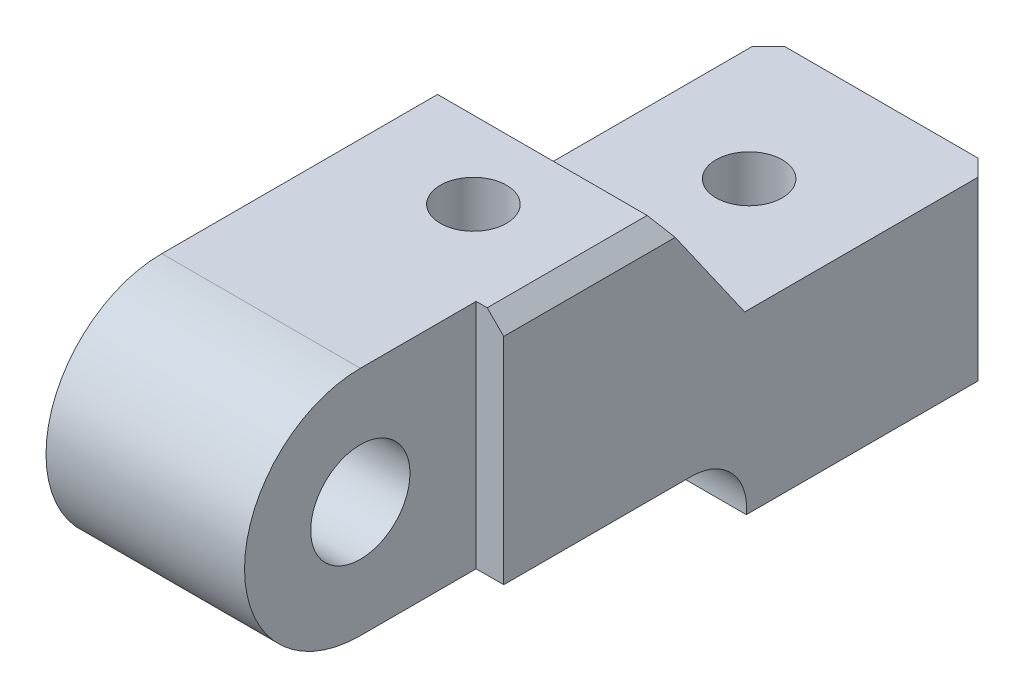
SolidWorks part; units mm, degrees
ref_plane "Front Plane" through (0, 0, 0) normal (0, 0, 1) x (1, 0, 0)
ref_plane "Top Plane" through (0, 0, 0) normal (0, 1, 0) x (1, 0, 0)
ref_plane "Right Plane" through (0, 0, 0) normal (1, 0, 0) x (0, 0, -1)
sketch "Sketch2" plane through (0, 0, 0) normal (1, 0, 0) x (0, 0, -1)
  line L0 (0, 21) -> (50, 21)
  line L1 (50, 21) -> (64.7044, 0)
  line L2 (64.7044, 0) -> (110, 0)
  line L3 (110, 0) -> (110, -32)
  line L4 (110, -32) -> (65, -32)
  line L5 (55.0501, -21) -> (0, -21)
  line L6 (50, 21) -> (75.2448, 21) construction
  circle A0 centre (0, 0) radius 9
  arc A1 (0, 21) -> (0, -21) centre (0, 0) ccw
  arc A2 (65, -32) -> (55.0501, -21) centre (55.0501, -31) ccw
  point P3 (0, 0)
  point P14 (0, 0)
  point P15 (0, 0)
  dimension "D1" = 18
  dimension "D2" = 21
  dimension "D7" = 10
  dimension "D3" = 50
  dimension "D4" = 55
  dimension "D5" = 32
  dimension "D6" = 45
  dimension "D8" = 110
extrude "Boss-Extrude1" add sketch "Sketch2" along normal mid plane 41
sketch "Sketch3" plane through (0, 21, 0) normal (0, 1, 0) x (1, 0, 0)
  line L0 (-20.5, -21) -> (15.5, -21)
  line L1 (-20.5, -21) -> (20.5, -21) construction
  line L2 (15.5, -21) -> (15.5, 21)
  line L3 (15.5, 21) -> (20.5, 21)
  line L4 (20.5, 50) -> (20.5, 0) construction
  line L5 (20.5, 21) -> (20.5, 110)
  line L6 (20.5, 110) -> (-20.5, 110)
  line L7 (-20.5, 110) -> (-20.5, -21)
  line L8 (0, 0) -> (0, 110) construction
  line L9 (15.5, -21) -> (20.5, -21)
  line L10 (20.5, -21) -> (20.5, 0) construction
  line L11 (20.5, -21) -> (20.5, 21)
  circle A0 centre (0, 36) radius 6
  circle A1 centre (0, 86) radius 6
  line M2 (-20.5, 0) -> (20.5, 0)
  line M3 (20.5, 0) -> (20.5, 50)
  dimension "D2" = 12
  dimension "D3" = 12
  dimension "D1" = 50
  dimension "D4" = 15
  dimension "D5" = 42
  dimension "D6" = 5
extrude "Cut-Extrude1" cut sketch "Sketch3" against normal through all contours L9 L11 L2 M2 | L3 L2 M2 M3 | A0 L8 | L8 A0 | A1 L8 | L8 A1
sketch "Sketch4" plane through (0, 0, -110) normal (0, 0, -1) x (-1, 0, 0)
  line L0 (0, 0) -> (0, -32) construction
  line L1 (-20.5, -32) -> (20.5, -32) construction
  line L2 (-6, -25) -> (6, -25)
  line L3 (-6, -25) -> (-6, -32)
  line L4 (6, -25) -> (6, -32)
  line L5 (-6, -32) -> (6, -32)
  point P8 (0, -25)
  dimension "D1" = 12
  dimension "D2" = 7
extrude "Cut-Extrude2" cut sketch "Sketch4" against normal through all
chamfer "Chamfer2" distance 3 angle 45 3 edges at (-20.5, -16, -110) (20.5, -16, -110) (20.5, 21, -35.5)
